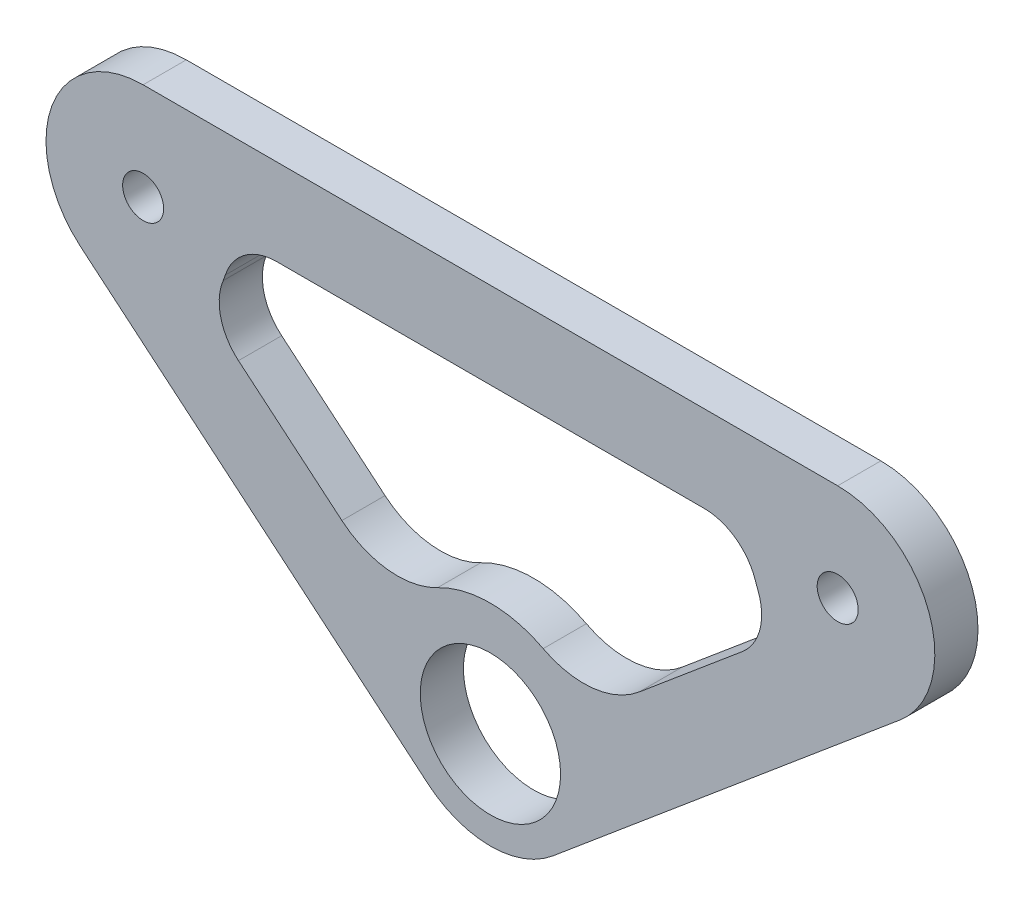
SolidWorks part; units mm, degrees
ref_plane "前视基准面" through (0, 0, 0) normal (0, 0, 1) x (1, 0, 0)
ref_plane "上视基准面" through (0, 0, 0) normal (0, 1, 0) x (1, 0, 0)
ref_plane "右视基准面" through (0, 0, 0) normal (1, 0, 0) x (0, 0, -1)
sketch "草图1" plane through (0, 0, 0) normal (0, 0, 1) x (1, 0, 0)
  line B0 (-32.1739, 35.9971) -> (32.1739, 35.9971)
  line B1 (37.959, 20.1027) -> (5.7851, -6.8944)
  line B2 (-5.7851, -6.8944) -> (-37.959, 20.1027)
  line B3 (23.3412, 18.2802) -> (13.7609, 10.2414)
  line B4 (-13.7609, 10.2414) -> (-23.3412, 18.2802)
  line B5 (-19.8045, 27.9971) -> (19.8045, 27.9971)
  arc B6 (4.8917, 9.2909) -> (13.7609, 10.2414) centre (8.6186, 16.3698) ccw
  arc B7 (-13.7609, 10.2414) -> (-4.8917, 9.2909) centre (-8.6186, 16.3698) ccw
  arc B8 (4.8917, 9.2909) -> (-4.8917, 9.2909) centre (0, 0) ccw
  circle B9 centre (0, 0) radius 6.5
  circle B10 centre (32.1739, 26.9971) radius 1.9
  circle B11 centre (-32.1739, 26.9971) radius 1.9
  arc B12 (-32.1739, 35.9971) -> (-37.959, 20.1027) centre (-32.1739, 26.9971) ccw
  arc B13 (-5.7851, -6.8944) -> (5.7851, -6.8944) centre (0, 0) ccw
  arc B14 (37.959, 20.1027) -> (32.1739, 35.9971) centre (32.1739, 26.9971) ccw
  arc B15 (-24.7606, 23.9899) -> (-24.562, 24.5355) centre (-32.1739, 26.9971) ccw
  arc B16 (24.562, 24.5355) -> (24.7606, 23.9899) centre (32.1739, 26.9971) ccw
  arc B17 (-19.8045, 27.9971) -> (-24.562, 24.5355) centre (-19.8045, 22.9971) ccw
  arc B18 (-24.7606, 23.9899) -> (-23.3412, 18.2802) centre (-20.1273, 22.1104) ccw
  arc B19 (23.3412, 18.2802) -> (24.7606, 23.9899) centre (20.1273, 22.1104) ccw
  arc B20 (24.562, 24.5355) -> (19.8045, 27.9971) centre (19.8045, 22.9971) ccw
sketch_block_instance "块1-1"
sketch_block "块1"
extrude "凸台-拉伸1" add sketch "草图1" along normal blind 4
